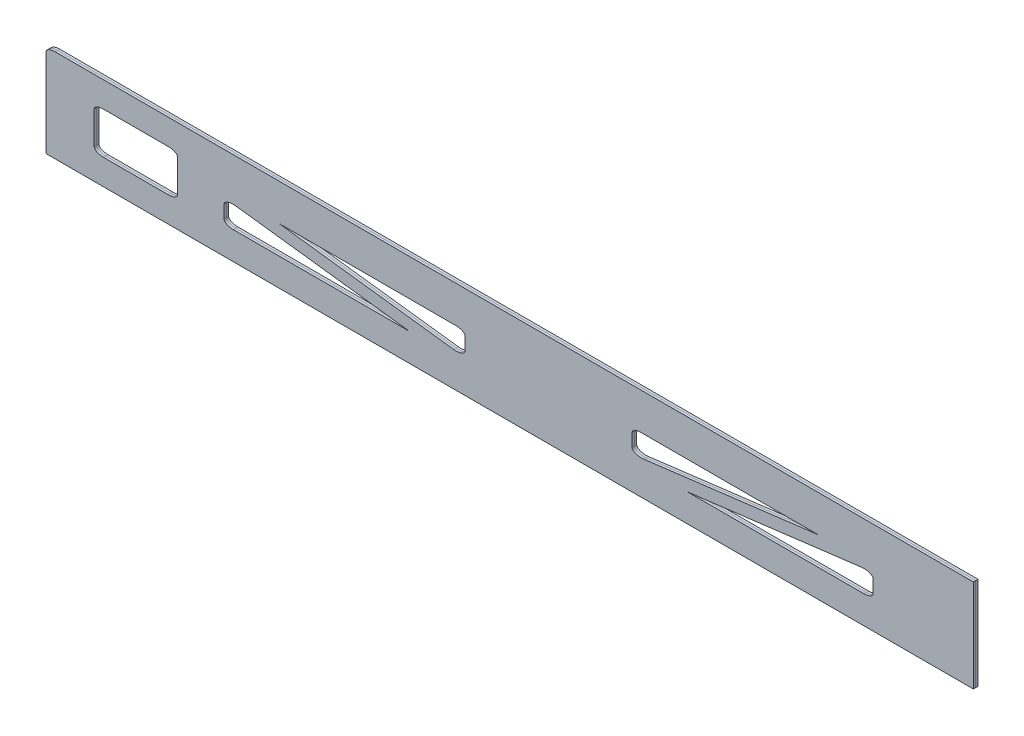
SolidWorks part; units mm, degrees
ref_plane "Front Plane" through (0, 0, 0) normal (0, 0, 1) x (1, 0, 0)
ref_plane "Top Plane" through (0, 0, 0) normal (0, 1, 0) x (1, 0, 0)
ref_plane "Right Plane" through (0, 0, 0) normal (1, 0, 0) x (0, 0, -1)
sketch "Sketch1" plane through (0, 0, 0) normal (0, 0, 1) x (1, 0, 0)
  line L0 (-200, 10) -> (-200, 20)
  line L1 (0, 0) -> (-200, 0) construction
  line L2 (0, 0) -> (0, 20) construction
  line L3 (0, 20) -> (-200, 20) construction
  line L4 (-200, 10) -> (-200, 20)
  line L5 (-100, 20) -> (-100, 0) construction
  line L6 (0, 10) -> (-200, 10) construction
  line L7 (-190, 0) -> (0, 0) construction
  line L8 (60.7449, 36.303) -> (260.1814, 21.3) construction
  line L9 (-180.8, 11) -> (-180.8, 6)
  line L10 (-194.8, 14.5) -> (-185.8, 14.5)
  line L11 (-194.8, 14.5) -> (-194.8, 5.5)
  line L12 (-194.8, 5.5) -> (-185.8, 5.5)
  line L13 (-185.8, 14.5) -> (-185.8, 5.5)
  line L14 (-190.3, 5.5) -> (-190.3, 14.5) construction
  line L15 (-194.8, 10) -> (-185.8, 10) construction
  line L16 (-180.8, 6) -> (-160.8, 6)
  line L17 (-160.8, 6) -> (-180.8, 11)
  line L18 (-175.1796, 10.8834) -> (-154.8, 5.7885) construction
  line L19 (-154.8, 7.0769) -> (-154.8, 12.0769)
  line L20 (-154.8, 12.0769) -> (-174.8, 12.0769)
  line L21 (-174.8, 12.0769) -> (-154.8, 7.0769)
  line L22 (-145.8, 16.5491) -> (-145.8, 2.1149) construction
  line L23 (-130.8, 6) -> (-110.8, 11)
  line L24 (-110.8, 6) -> (-130.8, 6)
  line L25 (-110.8, 11) -> (-110.8, 6)
  line L26 (-136.8, 7.0769) -> (-136.8, 12.0769)
  line L27 (-116.8, 12.0769) -> (-136.8, 7.0769)
  line L28 (-136.8, 12.0769) -> (-116.8, 12.0769)
  line L29 (-95.9515, 11.8485) -> (-89.8704, 5.7674) construction
  line L30 (-95.1029, 12.6971) -> (-89.0218, 6.6159)
  line L31 (-96.8, 11) -> (-90.7189, 4.9189)
  line L32 (-94.6431, 15.3485) -> (-89.9762, 10.6816) construction
  line L33 (-93.7946, 16.1971) -> (-89.1277, 11.5302)
  line L34 (-95.4917, 14.5) -> (-90.8248, 9.8331)
  line L35 (-76.1277, 16.7406) -> (-76.1277, 1.5062) construction
  line L36 (-60.9608, 18.25) -> (-63.9608, 18.25) construction
  line L37 (-91.2946, 19) -> (-88.2946, 19)
  line L38 (-91.2946, 19) -> (-91.2946, 17.5)
  line L39 (-91.2946, 17.5) -> (-88.2946, 17.5)
  line L40 (-88.2946, 19) -> (-88.2946, 17.5)
  line L41 (-89.7946, 17.5) -> (-89.7946, 19) construction
  line L42 (-91.2946, 18.25) -> (-88.2946, 18.25) construction
  line L43 (-62.4608, 17.5) -> (-62.4608, 19) construction
  line L44 (-63.9608, 19) -> (-63.9608, 17.5)
  line L45 (-60.9608, 17.5) -> (-63.9608, 17.5)
  line L46 (-60.9608, 19) -> (-60.9608, 17.5)
  line L47 (-60.9608, 19) -> (-63.9608, 19)
  line L48 (-57.6123, 15.3485) -> (-62.2792, 10.6816) construction
  line L49 (-58.4608, 16.1971) -> (-63.1277, 11.5302)
  line L50 (-56.7638, 14.5) -> (-61.4307, 9.8331)
  line L51 (-56.304, 11.8485) -> (-62.3851, 5.7674) construction
  line L52 (-57.1525, 12.6971) -> (-63.2336, 6.6159)
  line L53 (-55.4554, 11) -> (-61.5365, 4.9189)
  line L54 (-24.8204, 10.8834) -> (-45.2, 5.7885) construction
  line L55 (-25.2, 12.0769) -> (-45.2, 7.0769)
  line L56 (-45.2, 12.0769) -> (-25.2, 12.0769)
  line L57 (-45.2, 7.0769) -> (-45.2, 12.0769)
  line L58 (-39.2, 6) -> (-19.2, 11)
  line L59 (-19.2, 6) -> (-39.2, 6)
  line L60 (-19.2, 11) -> (-19.2, 6)
  line L61 (-200, 10) -> (-200, 0)
  line L62 (-200, 0) -> (-190, 0)
  line L63 (-10, 0) -> (-200, 0)
  line L64 (0, 20) -> (0, 10) construction
  line L65 (-10, 0) -> (0, 0)
  line L66 (0, 0) -> (0, 10)
  line L67 (-12.6863, 20) -> (-200, 20)
  line L68 (0, 10) -> (0, 0)
  line L69 (0, 10) -> (-1.9431, 15.3485)
  line L70 (-18.2706, 15.6552) -> (-15.2087, 11.7024) construction
  line L71 (-17.322, 16.3901) -> (-14.26, 12.4373)
  line L72 (-19.2193, 14.9203) -> (-16.1574, 10.9675)
  line L73 (-13.2706, 14.1721) -> (-10.2087, 10.2194) construction
  line L74 (-12.322, 14.907) -> (-9.26, 10.9542)
  line L75 (-14.2193, 13.4373) -> (-11.1574, 9.4845)
  line L76 (-8.2706, 14.6419) -> (-5.2087, 10.6891) construction
  line L77 (-7.322, 15.3767) -> (-4.26, 11.424)
  line L78 (-9.2193, 13.907) -> (-6.1574, 9.9542)
  arc A0 (-1.9431, 15.3485) -> (-12.6863, 20) centre (-12.6863, 5.2678) ccw
  arc A1 (-95.1029, 12.6971) -> (-96.8, 11) centre (-95.9515, 11.8485) ccw
  arc A2 (-90.7189, 4.9189) -> (-89.0218, 6.6159) centre (-89.8704, 5.7674) ccw
  arc A3 (-93.7946, 16.1971) -> (-95.4917, 14.5) centre (-94.6431, 15.3485) ccw
  arc A4 (-90.8248, 9.8331) -> (-89.1277, 11.5302) centre (-89.9762, 10.6816) ccw
  arc A5 (-58.4608, 16.1971) -> (-56.7638, 14.5) centre (-57.6123, 15.3485) cw
  arc A6 (-61.4307, 9.8331) -> (-63.1277, 11.5302) centre (-62.2792, 10.6816) cw
  arc A7 (-57.1525, 12.6971) -> (-55.4554, 11) centre (-56.304, 11.8485) cw
  arc A8 (-61.5365, 4.9189) -> (-63.2336, 6.6159) centre (-62.3851, 5.7674) cw
  arc A9 (-17.322, 16.3901) -> (-19.2193, 14.9203) centre (-18.2706, 15.6552) ccw
  arc A10 (-16.1574, 10.9675) -> (-14.26, 12.4373) centre (-15.2087, 11.7024) ccw
  arc A11 (-12.322, 14.907) -> (-14.2193, 13.4373) centre (-13.2706, 14.1721) ccw
  arc A12 (-11.1574, 9.4845) -> (-9.26, 10.9542) centre (-10.2087, 10.2194) ccw
  arc A13 (-7.322, 15.3767) -> (-9.2193, 13.907) centre (-8.2706, 14.6419) ccw
  arc A14 (-6.1574, 9.9542) -> (-4.26, 11.424) centre (-5.2087, 10.6891) ccw
  point P30 (-92.9109, 8.808)
  point P35 (-92.3097, 13.0151)
  point P45 (-89.1277, 9.8331)
  point P58 (-62.4608, 18.25)
  point P61 (-59.9457, 13.0151)
  point P68 (-59.3445, 8.808)
  point P86 (-16.7397, 13.6788)
  point P91 (-11.7397, 12.1958)
  point P98 (-6.7397, 12.6655)
  point P104 (-89.7946, 18.25)
  point P156 (-100, 10)
  point P158 (-190.3, 10)
  dimension "D3" = 200
  dimension "D12" = 11
  dimension "D13" = 9
  dimension "D14" = 1.2
  dimension "D27" = 1
  dimension "D28" = 1.2
  dimension "D1" = 200
  dimension "D2" = 20
  dimension "D4" = 9
  dimension "D5" = 5.2
  dimension "D6" = 9
  dimension "D7" = 20
  dimension "D8" = 5
  dimension "D9" = 5
  dimension "D10" = 1.25
  dimension "D11" = 9
  dimension "D15" = 14
  dimension "D16" = 45
  dimension "D17" = 1
  dimension "D18" = 13
  dimension "D19" = 3.5
  dimension "D20" = 3
  dimension "D21" = 1.5
  dimension "D22" = 1
  dimension "D23" = 2.5
  dimension "D24" = 6
  dimension "D25" = 70.034
  dimension "D26" = 1
  dimension "D29" = 5
  dimension "D30" = 5
  dimension "D31" = 5
extrude "Boss-Extrude1" add sketch "Sketch1" along normal mid plane 1 contours L69 A0 L67 L0 L61 L62 L63 L65 L66 A14 L78 A13 L77 A12 L75 A11 L74 A10 L72 A9 L71 A4 L34 A3 L33 A2 L31 A1 L30 L58 L60 L59 L55 L57 L56 L37 L40 L39 L38 L26 L28 L27
fillet "Fillet1" radius 10 2 edges at (-1.9431, 15.3485, 0) (0, 10, 0)
fillet "Fillet3" radius 1 17 edges at (-185.8, 5.5, 0) (-185.8, 14.5, 0) (-194.8, 14.5, 0) (-194.8, 5.5, 0) (-19.2, 11, 0) (-19.2, 6, 0) (-45.2, 7.0769, 0) (-45.2, 12.0769, 0) (-110.8, 11, 0) (-110.8, 6, 0) (-136.8, 12.0769, 0) (-136.8, 7.0769, 0) (-154.8, 12.0769, 0) (-154.8, 7.0769, 0) (-180.8, 11, 0) (-180.8, 6, 0) (-200, 20, 0)
ref_plane "Plane2" through (0, 0, 0) normal (0, 0, 1) x (1, 0, 0)
split "Split1" trim tools "Plane2" bodies to split 101 resulting bodies 104 105
split "Split2" trim tools "Plane2" bodies to split 105 104 resulting bodies 106 107
scale "Scale2" bodies to scale 107 106 scale about centroid uniform scaling no x scale factor 2 y scale factor 1 z scale factor 1
sketch "Sketch3" plane through (0, 0, 0.5) normal (0, 0, 1) x (1, 0, 0)
  line L1 (100.0405, 0) -> (-99.9595, 0)
  line L2 (100.0405, 0) -> (100.0405, 40.0847)
  line L3 (100.0405, 40.0847) -> (-99.9595, 40.0847)
  line L4 (-99.9595, 0) -> (-99.9595, 40.0847)
  dimension "D1" = 200
extrude "Cut-Extrude2" cut sketch "Sketch3" against normal through all both and the other way through all
